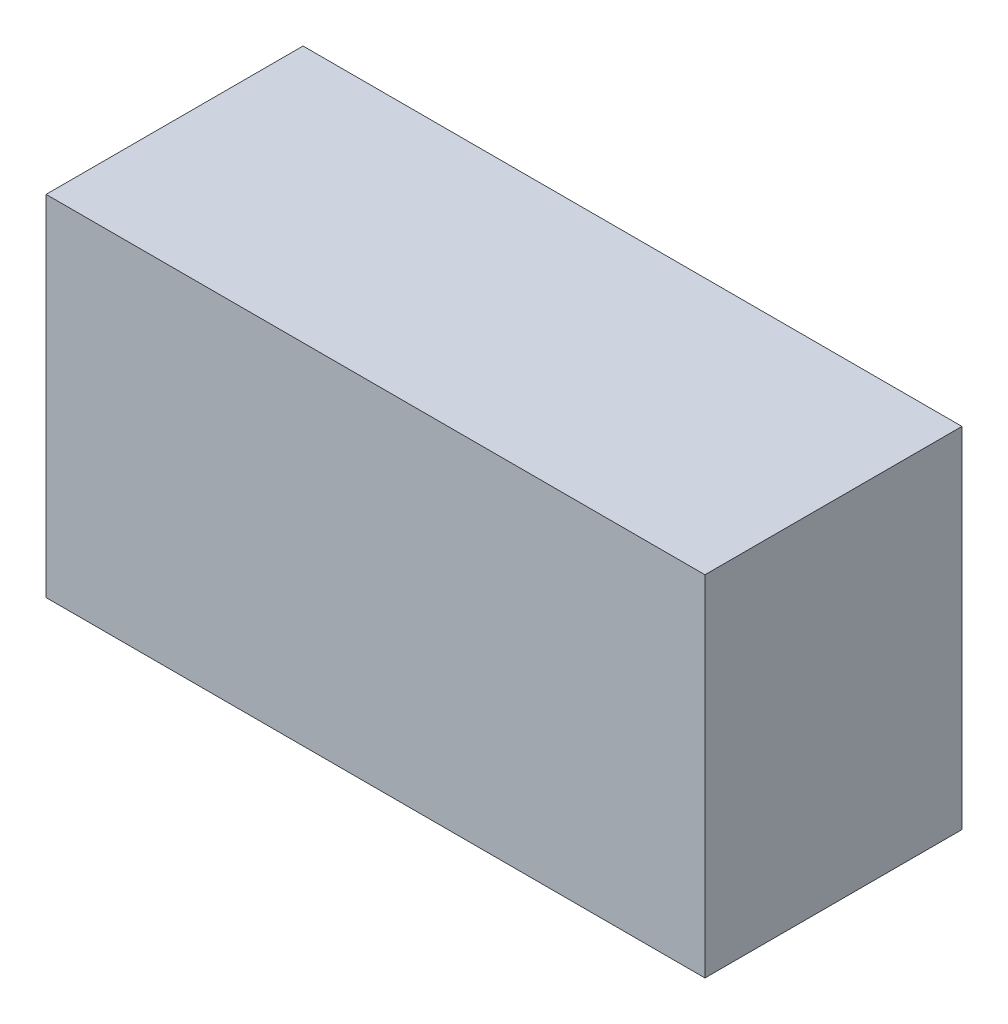
SolidWorks part; units mm, degrees
ref_plane "前视基准面" through (0, 0, 0) normal (0, 0, 1) x (1, 0, 0)
ref_plane "上视基准面" through (0, 0, 0) normal (0, 1, 0) x (1, 0, 0)
ref_plane "右视基准面" through (0, 0, 0) normal (1, 0, 0) x (0, 0, -1)
other "Configuration Table"
sketch "草图1" plane through (0, 0, 0) normal (0, 1, 0) x (1, 0, 0)
  line L1 (0, 0) -> (100, 0)
  line L2 (0, 0) -> (0, -39)
  line L3 (0, -39) -> (100, -39)
  line L4 (100, 0) -> (100, -39)
  dimension "D1" = 100
  dimension "D2" = 39
extrude "凸台-拉伸1" add sketch "草图1" along normal blind 53
